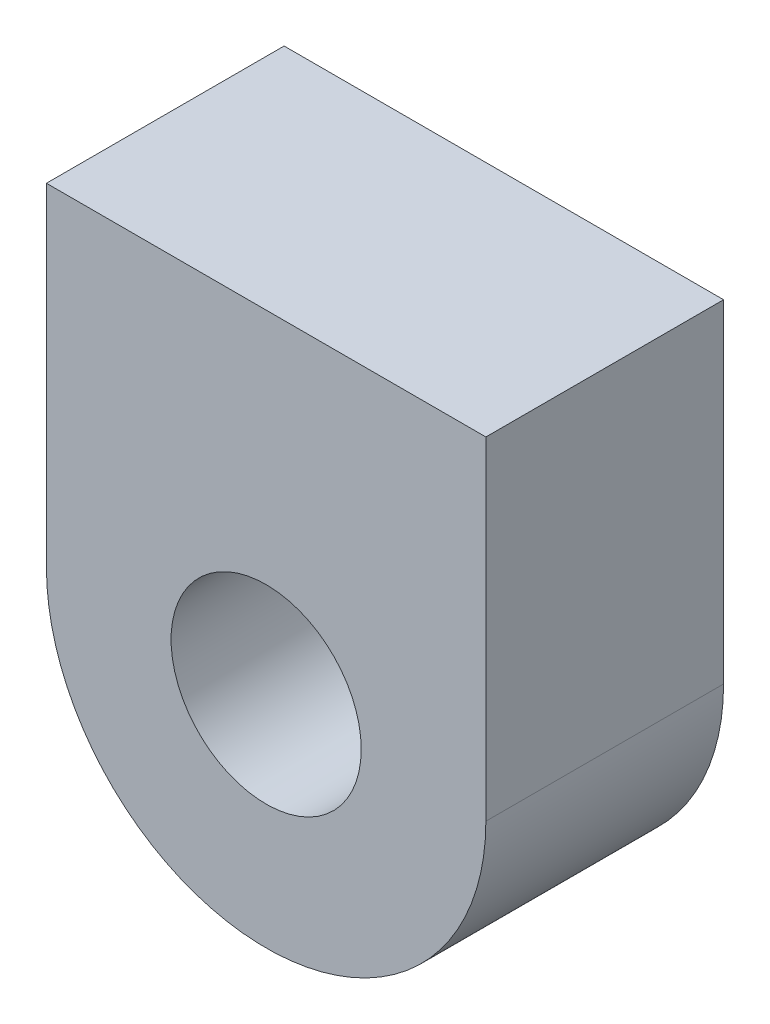
SolidWorks part; units mm, degrees
ref_plane "Front Plane" through (0, 0, 0) normal (0, 0, 1) x (1, 0, 0)
ref_plane "Top Plane" through (0, 0, 0) normal (0, 1, 0) x (1, 0, 0)
ref_plane "Right Plane" through (0, 0, 0) normal (1, 0, 0) x (0, 0, -1)
sketch "Sketch3" plane through (0, 0, 0) normal (0, 0, 1) x (1, 0, 0)
  line L0 (-4.622, 7) -> (-4.622, 0)
  line L1 (4.622, 7) -> (4.622, 0)
  line L2 (-4.622, 7) -> (4.622, 7)
  arc A0 (-4.622, 0) -> (4.622, 0) centre (0, 0) ccw
  circle A1 centre (0, 0) radius 2
  point P7 (0, 0)
  point P8 (0, 0)
  dimension "D1" = 4
  dimension "D2" = 7
  dimension "D3" = 7
  dimension "D4" = 9.2441
extrude "Boss-Extrude2" add sketch "Sketch3" along normal blind 5
